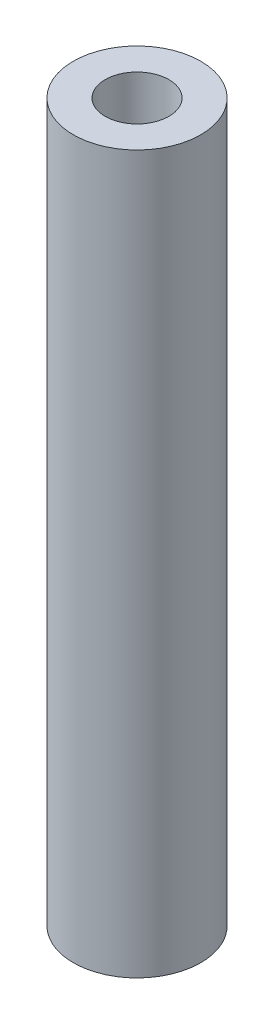
SolidWorks part; units mm, degrees
ref_plane "Front" through (0, 0, 0) normal (0, 0, 1) x (1, 0, 0)
ref_plane "Top" through (0, 0, 0) normal (0, 1, 0) x (1, 0, 0)
ref_plane "Right" through (0, 0, 0) normal (1, 0, 0) x (0, 0, -1)
sketch "Sketch1" plane through (0, 0, 0) normal (0, 1, 0) x (1, 0, 0)
  circle A0 centre (0, 0) radius 2
  circle A1 centre (0, 0) radius 4
  dimension "D1" = 8
  dimension "D2" = 4
extrude "Boss-Extrude1" add sketch "Sketch1" along normal blind 45
